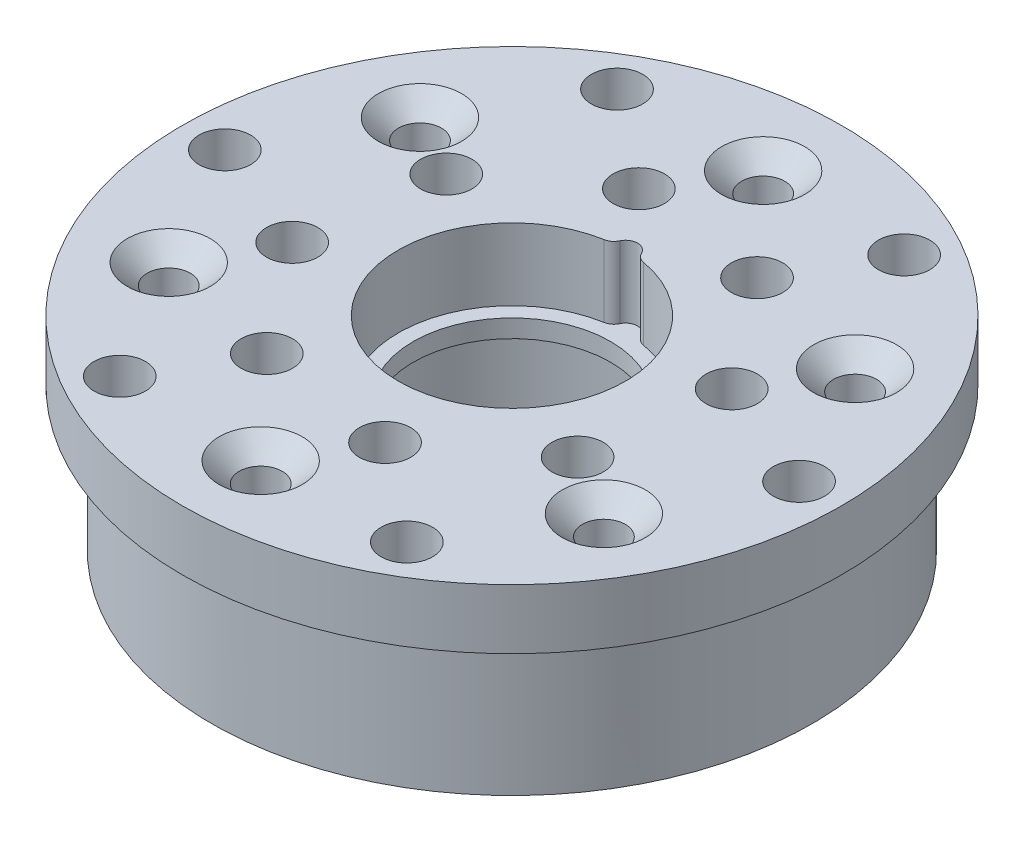
SolidWorks part; units mm, degrees
ref_plane "Front Plane" through (0, 0, 0) normal (0, 0, 1) x (1, 0, 0)
ref_plane "Top Plane" through (0, 0, 0) normal (0, 1, 0) x (1, 0, 0)
ref_plane "Right Plane" through (0, 0, 0) normal (1, 0, 0) x (0, 0, -1)
sketch "Sketch1" plane through (0, 0, 0) normal (0, 1, 0) x (1, 0, 0)
  circle A0 centre (0, 0) radius 21 construction
  circle A1 centre (0, 21) radius 2.5
  circle A2 centre (18.1865, 10.5) radius 2.5
  circle A3 centre (18.1865, -10.5) radius 2.5
  circle A4 centre (0, -21) radius 2.5
  circle A5 centre (-18.1865, -10.5) radius 2.5
  circle A6 centre (-18.1865, 10.5) radius 2.5
  circle A7 centre (0, 0) radius 25.1
  circle A8 centre (0, 0) radius 8.25
  point P18 (0, 0)
  dimension "D1" = 42
  dimension "D2" = 5
  dimension "D4" = 50.2
  dimension "D5" = 16.5
  dimension "D3" = 6
extrude "Boss-Extrude1" add sketch "Sketch1" along normal blind 10
sketch "Sketch2" plane through (0, 10, 0) normal (0, 1, 0) x (1, 0, 0)
  circle A0 centre (0, 0) radius 9.5
  circle A1 centre (0, 0) radius 15.5
  dimension "D1" = 19
  dimension "D2" = 6
extrude "Boss-Extrude2" add sketch "Sketch2" along normal blind 8.5
sketch "Sketch4" plane through (0, 10, 0) normal (0, 1, 0) x (1, 0, 0)
  circle A0 centre (0, 0) radius 9.5 construction
  circle A1 centre (0, 0) radius 8.25 construction
  circle A2 centre (0, 0) radius 9.5
  circle A3 centre (0, 0) radius 8.25
extrude "Boss-Extrude3" add sketch "Sketch4" along normal blind 2.5
sketch "Sketch3" plane through (0, 0, 0) normal (0, -1, 0) x (1, 0, 0)
  circle A0 centre (0, 0) radius 12.5
  dimension "D1" = 25
extrude "Cut-Extrude1" cut sketch "Sketch3" against normal blind 11
chamfer "Chamfer1" distance 3 angle 45 1 edges at (0, 11, -12.5)
sketch "Sketch5" plane through (0, 10, 0) normal (0, 1, 0) x (1, 0, 0)
  circle A0 centre (0, 21) radius 2.5
  circle A1 centre (18.1872, 10.4996) radius 2.5
  circle A2 centre (18.1872, -10.5011) radius 2.5
  circle A3 centre (0, -21.0014) radius 2.5
  circle A4 centre (-18.1872, -10.5011) radius 2.5
  circle A5 centre (-18.1872, 10.4996) radius 2.5
  circle A6 centre (0, 0) radius 25.1 construction
  circle A7 centre (0, 0) radius 25.1
  circle A8 centre (0, 0) radius 15.5 construction
  circle A9 centre (0, 0) radius 15.5
  circle A10 centre (0, 21) radius 2.5 construction
  point P15 (0, -0.0007)
  dimension "D2" = 6
extrude "Boss-Extrude4" add sketch "Sketch5" along normal blind 8.5
sketch "Sketch6" plane through (0, 18.5, 0) normal (0, 1, 0) x (1, 0, 0)
  circle A0 centre (0, 0) radius 25.1 construction
  circle A1 centre (0, 0) radius 25.1
  circle A2 centre (0, 0) radius 27.55
  dimension "D1" = 55.1
extrude "Boss-Extrude5" add sketch "Sketch6" against normal blind 5
sketch "Sketch8" plane through (0, 18.5, 0) normal (0, 1, 0) x (1, 0, 0)
  circle A0 centre (0, 9.5) radius 1
  circle A1 centre (0, 0) radius 9.5 construction
  circle A2 centre (0, 0) radius 9.5 construction
  dimension "D1" = 2
extrude "Cut-Extrude2" cut sketch "Sketch8" against normal up to surface (6 mm away) up to face at (0, 12.5, 9.5)
fillet "Fillet1" radius 1 2 edges at (0.9986, 15.5, -9.4474) (-0.9986, 15.5, -9.4474)
sketch "Sketch11" plane through (0, 18.5, 0) normal (0, 1, 0) x (1, 0, 0)
  line L0 (0, 0) -> (17.55, 30.3975) construction
  circle A0 centre (0, 0) radius 15 construction
  circle A1 centre (7.5, 12.9904) radius 2.15
  circle A2 centre (14.4889, 3.8823) radius 2.15
  circle A3 centre (12.9904, -7.5) radius 2.15
  circle A4 centre (3.8823, -14.4889) radius 2.15
  circle A5 centre (-7.5, -12.9904) radius 2.15
  circle A6 centre (-14.4889, -3.8823) radius 2.15
  circle A7 centre (0, 0) radius 24 construction
  circle A8 centre (-24, 0) radius 2.15
  circle A9 centre (-12, 20.7846) radius 2.15
  circle A10 centre (12, 20.7846) radius 2.15
  circle A11 centre (24, 0) radius 2.15
  circle A12 centre (12, -20.7846) radius 2.15
  circle A13 centre (-12, -20.7846) radius 2.15
  circle A14 centre (-12.9904, 7.5) radius 2.15
  circle A15 centre (-3.8823, 14.4889) radius 2.15
  point P18 (0, 0)
  point P32 (0, 0)
  dimension "D2" = 30
  dimension "D3" = 4.3
  dimension "D5" = 48
  dimension "D1" = 60
  dimension "D4" = 8
extrude "Cut-Extrude3" cut sketch "Sketch11" against normal blind 4.8
sketch "Sketch12" plane through (0, 0, 0) normal (0, -1, 0) x (1, 0, 0)
  circle A0 centre (0, 0) radius 25.1 construction
  circle A1 centre (18.1865, 10.5) radius 2.5 construction
  circle A2 centre (18.1865, -10.5) radius 2.5 construction
  circle A3 centre (0, -21) radius 2.5 construction
  circle A4 centre (-18.1865, -10.5) radius 2.5 construction
  circle A5 centre (-18.1865, 10.5) radius 2.5 construction
  circle A6 centre (0, 21) radius 2.5 construction
  circle A7 centre (0, 0) radius 12.5 construction
  circle A8 centre (0, 0) radius 25.1
  circle A9 centre (18.1865, 10.5) radius 2.5
  circle A10 centre (18.1865, -10.5) radius 2.5
  circle A11 centre (0, -21) radius 2.5
  circle A12 centre (-18.1865, -10.5) radius 2.5
  circle A13 centre (-18.1865, 10.5) radius 2.5
  circle A14 centre (0, 21) radius 2.5
  circle A15 centre (0, 0) radius 12.5
extrude "Cut-Extrude4" cut sketch "Sketch12" against normal blind 1.5
sketch "Sketch14" plane through (0, 18.5, 0) normal (0, 1, 0) x (1, 0, 0)
  circle A0 centre (0, 21) radius 2.5 construction
  circle A1 centre (0, 21) radius 2.5
  circle A2 centre (0, 21) radius 1.5
  circle A3 centre (18.1872, 10.4996) radius 1.5
  circle A4 centre (18.1872, 10.4996) radius 2.5
  circle A5 centre (18.1872, -10.5011) radius 1.5
  circle A6 centre (18.1872, -10.5011) radius 2.5
  circle A7 centre (0, -21.0014) radius 1.5
  circle A8 centre (0, -21.0014) radius 2.5
  circle A9 centre (-18.1872, -10.5011) radius 1.5
  circle A10 centre (-18.1872, -10.5011) radius 2.5
  circle A11 centre (-18.1872, 10.4996) radius 1.5
  circle A12 centre (-18.1872, 10.4996) radius 2.5
  point P22 (0, -0.0007)
  dimension "D1" = 3
extrude "Boss-Extrude8" add sketch "Sketch14" against normal blind 4.5
hole_wizard "CSK for M3 socket countersunk head screw1" positions "Sketch15" profile "Sketch16" countersink size "M3" standard "DIN" end condition through all
sketch "Sketch15" plane through (0, 18.5, 0) normal (0, 1, 0) x (1, 0, 0)
  point P0 (0, 21)
  point P3 (18.1872, 10.4996)
  point P6 (18.1872, -10.5011)
  point P9 (0, -21.0014)
  point P12 (-18.1872, -10.5011)
  point P15 (-18.1872, 10.4996)
sketch "Sketch16" plane through (0, 18.5, -21) normal (1, 0, 0) x (0, 0, 1)
  line L0 (0, 0) -> (0, 17)
  line L1 (0, 17) -> (1.8, 17)
  line L2 (1.8, 17) -> (1.8, 1.67)
  line L3 (1.8, 1.67) -> (3.47, 0)
  line L5 (3.47, 0) -> (0, 0)
  line L6 (-1.8, 1.67) -> (-3.47, 0) construction
  line L11 (0, -6.35) -> (0, 107.95) construction
  dimension "Thru Hole Dia." = 3.6
  dimension "Thru Hole Depth" = 17
  dimension "Near C'Sink Dia." = 6.94
  dimension "Near C'Sink Angle" = 90
